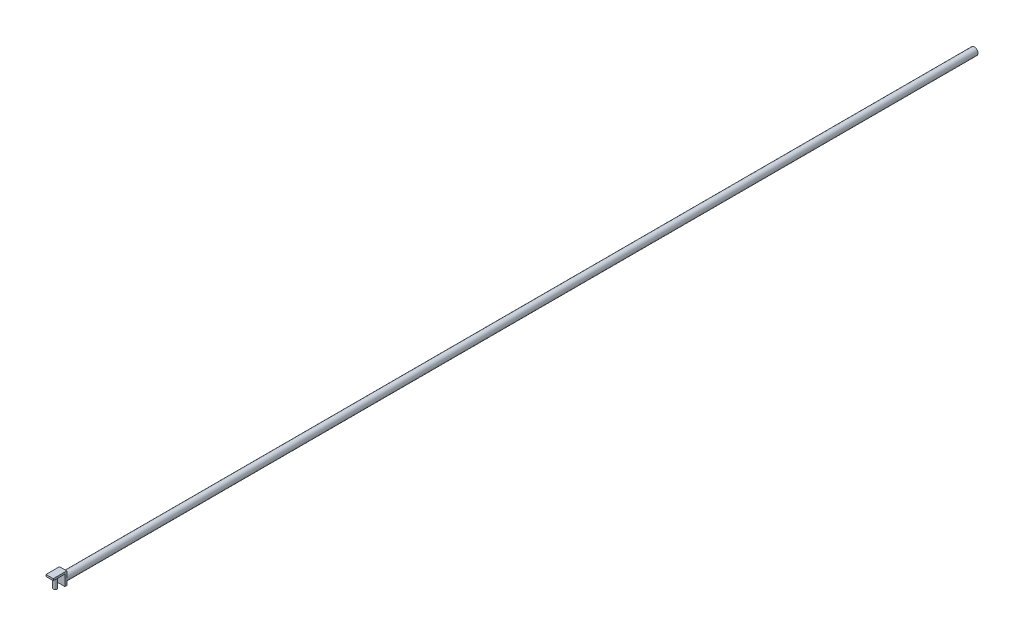
SolidWorks part; units mm, degrees
ref_plane "Front" through (0, 0, 0) normal (0, 0, 1) x (1, 0, 0)
ref_plane "Top" through (0, 0, 0) normal (0, 1, 0) x (1, 0, 0)
ref_plane "Right" through (0, 0, 0) normal (1, 0, 0) x (0, 0, -1)
sketch "草图1" plane through (0, 0, 0) normal (0, 0, 1) x (1, 0, 0)
  line L0 (-1.775, 0) -> (1.6783, 0) construction
  line L1 (0, 1.1841) -> (0, -1.5559) construction
  line L3 (-1, 1.5) -> (1, 1.5)
  line L4 (-1, 1.5) -> (-1, -1.5)
  line L5 (-1, -1.5) -> (1, -1.5)
  line L6 (1, 1.5) -> (1, -1.5)
  dimension "D1" = 2
  dimension "D2" = 3
  dimension "D3" = 1
  dimension "D4" = 1.5
extrude "凸台-拉伸1" add sketch "草图1" along normal blind 0.5
sketch "草图2" plane through (0, 1.5, 0) normal (0, 1, 0) x (1, 0, 0)
  line L1 (-1, 0) -> (1, 0)
  line L2 (-1, 0) -> (-1, -3.7)
  line L3 (-1, -3.7) -> (1, -3.7)
  line L4 (1, 0) -> (1, -3.7)
  dimension "D1" = 2
  dimension "D2" = 3.7
extrude "凸台-拉伸2" add sketch "草图2" along normal blind 0.5
sketch "草图3" plane through (0, 0, 0) normal (0, 0, -1) x (-1, 0, 0)
  circle A0 centre (0, 0) radius 1
  dimension "D1" = 2
extrude "凸台-拉伸3" add sketch "草图3" along normal blind 250
sketch "草图4" plane through (0, 1.5, 0) normal (0, -1, 0) x (1, 0, 0)
  line L0 (-1, 0.5) -> (-1, 3.7) construction
  line L1 (-1, 3.7) -> (1, 3.7) construction
  circle A0 centre (0, 2.2) radius 0.5
  dimension "D1" = 1
  dimension "D2" = 1
  dimension "D3" = 1.5
extrude "凸台-拉伸4" add sketch "草图4" along normal blind 3
